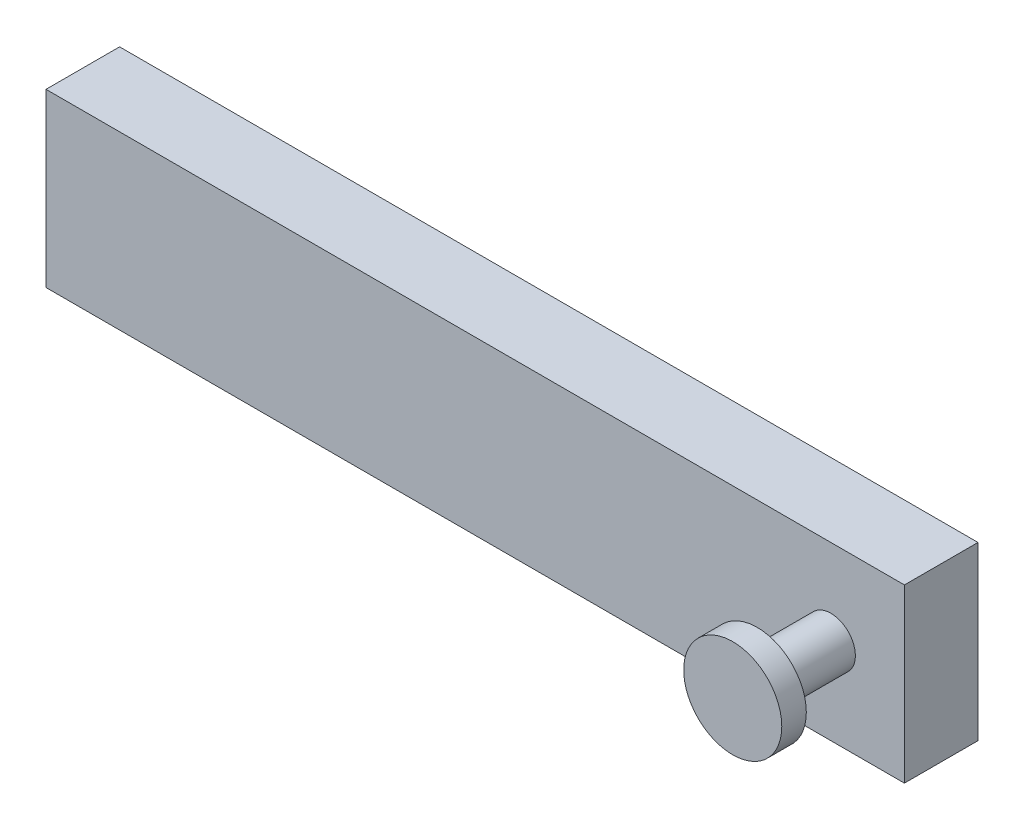
SolidWorks part; units mm, degrees
ref_plane "Alzado" through (0, 0, 0) normal (0, 0, 1) x (1, 0, 0)
ref_plane "Planta" through (0, 0, 0) normal (0, 1, 0) x (1, 0, 0)
ref_plane "Vista lateral" through (0, 0, 0) normal (1, 0, 0) x (0, 0, -1)
sketch "Croquis1" plane through (0, 0, 0) normal (0, 0, 1) x (1, 0, 0)
  line L1 (0, 0) -> (350, 0)
  line L2 (0, 0) -> (0, 70)
  line L3 (0, 70) -> (350, 70)
  line L4 (350, 0) -> (350, 70)
  dimension "D1" = 350
  dimension "D2" = 70
extrude "Saliente-Extruir1" add sketch "Croquis1" along normal blind 30
sketch "Croquis2" plane through (0, 0, 30) normal (0, 0, 1) x (1, 0, 0)
  line L0 (350, 70) -> (0, 70) construction
  line L1 (350, 0) -> (350, 70) construction
  circle A0 centre (320, 35) radius 20
  dimension "D1" = 40
  dimension "D2" = 35
  dimension "D3" = 30
extrude "Saliente-Extruir2" add sketch "Croquis2" along normal blind 40
sketch "Croquis4" plane through (0, 0, 30) normal (0, 0, 1) x (1, 0, 0)
  circle A0 centre (320, 35) radius 20
  circle A1 centre (320, 35) radius 10
  dimension "D1" = 20
extrude "Cortar-Extruir1" cut sketch "Croquis4" along normal blind 30
